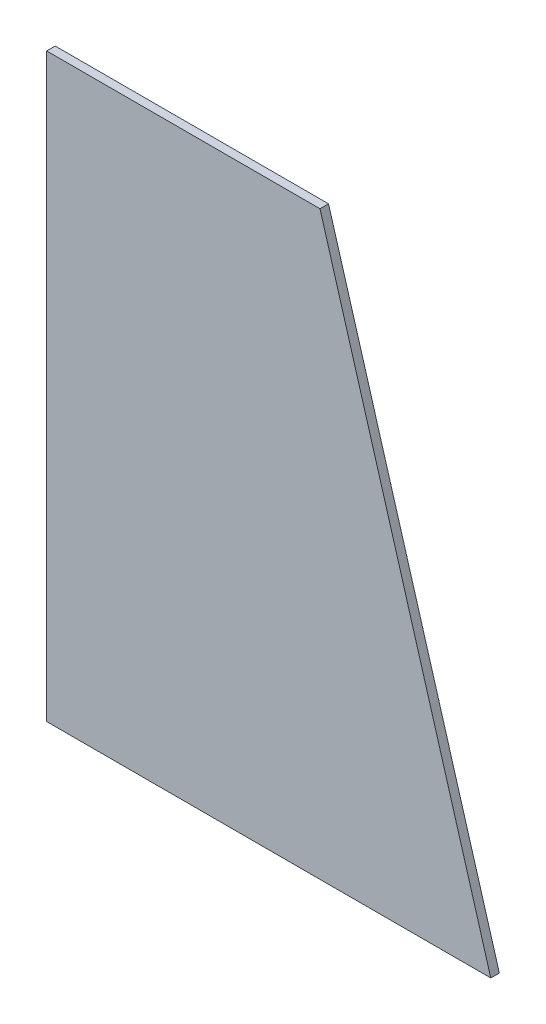
SolidWorks part; units mm, degrees
material "PVC 0.007 Plasticized"
ref_plane "Front Plane" through (0, 0, 0) normal (0, 0, 1) x (1, 0, 0)
ref_plane "Top Plane" through (0, 0, 0) normal (0, 1, 0) x (1, 0, 0)
ref_plane "Right Plane" through (0, 0, 0) normal (1, 0, 0) x (0, 0, -1)
sketch "Sketch1" plane through (0, 0, 0) normal (0, 0, 1) x (1, 0, 0)
  line L5 (0, 107.95) -> (101.6, 107.95)
  line L6 (0, -107.95) -> (165.1, -107.95)
  line L10 (0, 107.95) -> (0, -107.95)
  line L11 (101.6, 107.95) -> (165.1, -107.95)
  point P0 (0, 0)
  dimension "D1" = 101.6
  dimension "D2" = 165.1
  dimension "D3" = 215.9
extrude "Boss-Extrude1" add sketch "Sketch1" against normal blind 3.175
